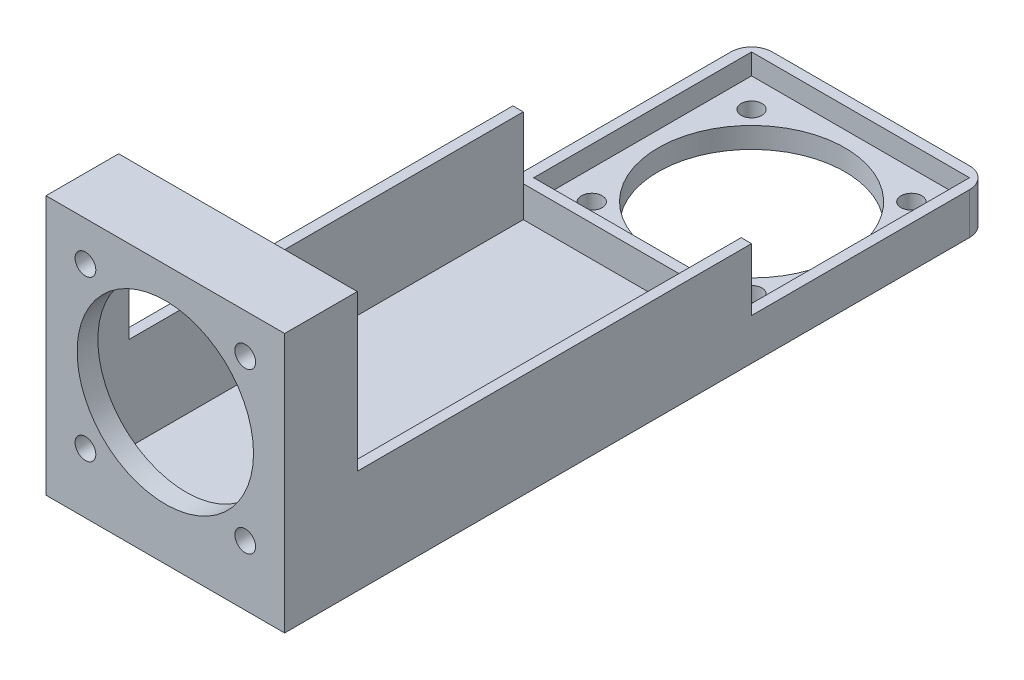
SolidWorks part; units mm, degrees
material "5052-H32"
ref_plane "前视基准面" through (0, 0, 0) normal (0, 0, 1) x (1, 0, 0)
ref_plane "上视基准面" through (0, 0, 0) normal (0, 1, 0) x (1, 0, 0)
ref_plane "右视基准面" through (0, 0, 0) normal (1, 0, 0) x (0, 0, -1)
sketch "草图1" plane through (0, 0, 0) normal (0, 1, 0) x (1, 0, 0)
  line L1 (0, 0) -> (21, 0)
  line L2 (0, 0) -> (0, 21)
  line L3 (0, 21) -> (21, 21)
  line L4 (21, 0) -> (21, 21)
  line L7 (-1, -1) -> (22, -1)
  line L8 (-1, -1) -> (-1, 22)
  line L9 (-1, 22) -> (22, 22)
  line L10 (22, -1) -> (22, 22)
extrude "凸台-拉伸1" add sketch "草图1" along normal blind 4
sketch "草图2" plane through (0, 0, 0) normal (0, 1, 0) x (1, 0, 0)
  line L0 (0, 0) -> (21, 0) construction
  line L1 (0, 21) -> (21, 21)
  line L2 (0, 21) -> (0, 0)
  line L3 (0, 0) -> (21, 0)
  line L4 (21, 21) -> (21, 0)
  line L5 (21, 0) -> (21, 21) construction
extrude "凸台-拉伸2" add sketch "草图2" along normal blind 2 contours L2 L1 L4 L3
sketch "草图3" plane through (0, 2, 0) normal (0, 1, 0) x (1, 0, 0)
  line L0 (0, 10.5) -> (21, 10.5)
  line L1 (0, 21) -> (0, 0) construction
  line L2 (21, 0) -> (21, 21) construction
  circle A0 centre (10.5, 10.5) radius 9
extrude "切除-拉伸1" cut sketch "草图3" against normal blind 2 contours L0 A0 | L0 A0
sketch "草图4" plane through (0, 2, 0) normal (0, 1, 0) x (1, 0, 0)
  line L0 (-1, -1) -> (22, -1)
  line L3 (0, 0) -> (21, 0)
  circle A4 centre (18.2, 2.8) radius 1
  circle A5 centre (18.2, 18.2) radius 1
  circle A6 centre (2.8, 18.2) radius 1
  circle A7 centre (2.8, 2.8) radius 1
sketch "草图5" plane through (0, 4, 0) normal (0, 1, 0) x (1, 0, 0)
  line L0 (0, 0) -> (0, 10)
  line L1 (0, 21) -> (0, 0) construction
  line L2 (0, 10) -> (-1, 10)
  line L3 (-1, 22) -> (-1, -1) construction
  line L4 (-1, 10) -> (-1, -1)
  line L5 (-1, -1) -> (22, -1)
  line L6 (22, -1) -> (22, 10)
  line L7 (22, -1) -> (22, 22) construction
  line L8 (22, 10) -> (21, 10)
  line L9 (21, 21) -> (21, 0) construction
  line L10 (21, 10) -> (21, 0)
  line L11 (21, 0) -> (0, 0)
fillet "圆角2" radius 2 1 edges at (-1, 2, -22)
fillet "圆角3" radius 2 1 edges at (22, 2, -22)
sketch "草图18" plane through (0, 0, 1) normal (0, 0, 1) x (1, 0, 0)
  line L0 (-1, 0) -> (22, 0)
  line L1 (22, 0) -> (22, 10)
  line L2 (22, 4) -> (22, 0) construction
  line L3 (-1, 0) -> (-1, 10)
  line L4 (-1, 4) -> (-1, 0) construction
  line L5 (-1, 10) -> (0, 10)
  line L6 (0, 10) -> (0, 1)
  line L7 (0, 1) -> (21, 1)
  line L8 (21, 1) -> (21, 10)
  line L9 (21, 10) -> (22, 10)
extrude "凸台-拉伸6" add sketch "草图18" along normal blind 45
sketch "草图19" plane through (0, 1, 0) normal (0, 1, 0) x (1, 0, 0)
  line L0 (-1, -46) -> (22, -46)
  line L1 (22, -46) -> (22, -44)
  line L3 (22, -46) -> (22, -1) construction
  line L4 (22, -44) -> (-1, -44)
  line L5 (-1, -46) -> (-1, -1) construction
  line L6 (-1, -44) -> (-1, -46)
extrude "凸台-拉伸7" add sketch "草图19" along normal blind 24
sketch "草图22" plane through (0, 0, 46) normal (0, 0, 1) x (1, 0, 0)
  line L0 (-1, 25) -> (10.5, 25)
  line L8 (-1, 25) -> (22, 25) construction
  circle A10 centre (10.5, 13.5) radius 8.5
  circle A11 centre (18.2, 21.2) radius 1
  circle A12 centre (2.8, 21.2) radius 1
  circle A13 centre (2.8, 5.8) radius 1
  circle A14 centre (18.2, 5.8) radius 1
sketch "草图23" plane through (0, 2, 0) normal (0, 1, 0) x (1, 0, 0)
  line L0 (21, 21) -> (21, 0)
extrude "切除-拉伸9" cut sketch "草图4" against normal blind 20 contours A6 | A7 | A4 | A5
sketch "草图24" plane through (0, 0, 44) normal (0, 0, -1) x (-1, 0, 0)
  line L0 (-22, 10) -> (-22, 25)
  line L1 (-22, 25) -> (1, 25)
  line L2 (1, 25) -> (1, 10)
  line L3 (1, 10) -> (0, 10)
  line L4 (0, 10) -> (0, 24)
  line L5 (0, 24) -> (-21, 24)
  line L6 (-21, 24) -> (-21, 10)
  line L15 (-22, 25) -> (-22, 10)
  line L16 (-22, 10) -> (-21, 10)
  line L17 (-21, 10) -> (-21, 1)
  line L18 (-21, 1) -> (0, 1)
  line L19 (0, 1) -> (0, 10)
  line L20 (0, 10) -> (1, 10)
  line L21 (1, 10) -> (1, 25)
  line L22 (1, 25) -> (-22, 25)
  line L24 (-22, 10) -> (-21, 10)
  dimension "D1" = 0
extrude "凸台-拉伸8" add sketch "草图24" along normal blind 5
extrude "切除-拉伸11" cut sketch "草图22" against normal blind 5
